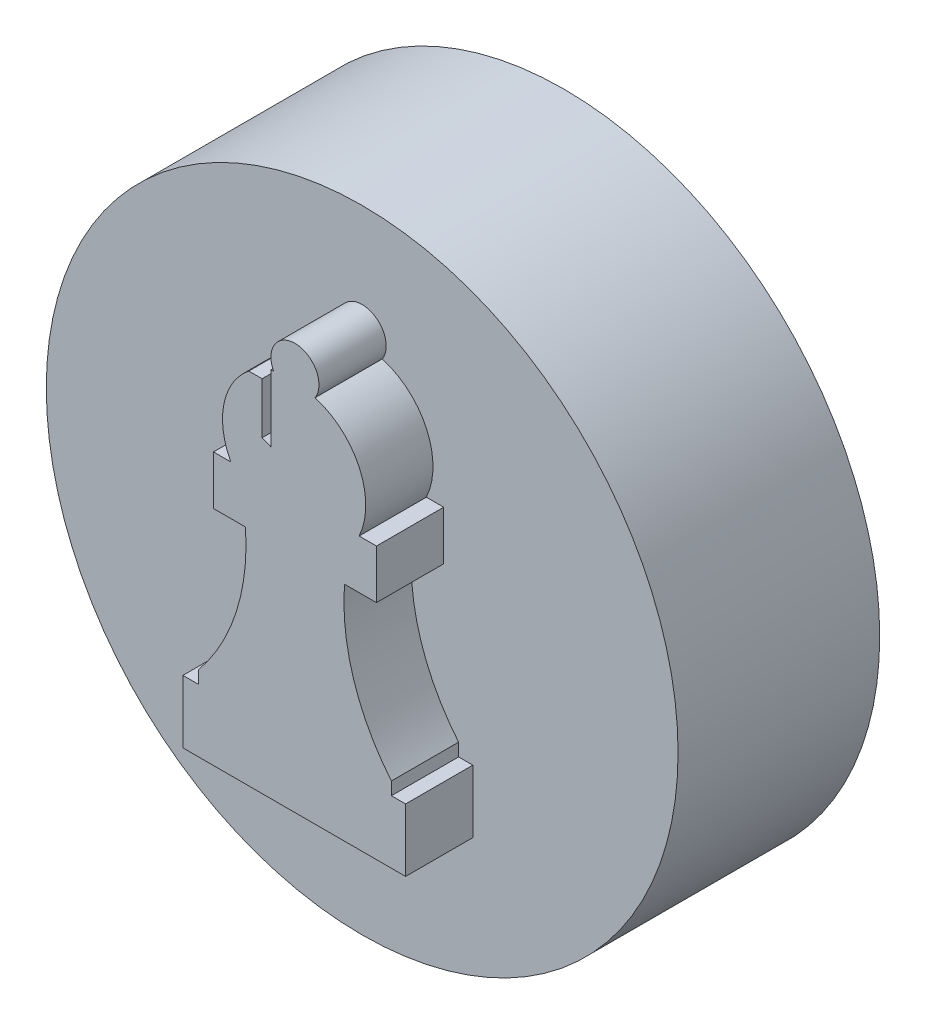
SolidWorks part; units mm, degrees
ref_plane "Front Plane" through (0, 0, 0) normal (0, 0, 1) x (1, 0, 0)
ref_plane "Top Plane" through (0, 0, 0) normal (0, 1, 0) x (1, 0, 0)
ref_plane "Right Plane" through (0, 0, 0) normal (1, 0, 0) x (0, 0, -1)
sketch "Sketch1" plane through (0, 0, 0) normal (0, 0, 1) x (1, 0, 0)
  circle A0 centre (0, 0) radius 8.763
  circle A1 centre (0, 0) radius 11.938
  dimension "D1" = 17.526
  dimension "D2" = 23.876
extrude "Boss-Extrude1" add sketch "Sketch1" along normal blind 5.08
sketch "Sketch2" plane through (0, 0, 5.08) normal (0, 0, 1) x (1, 0, 0)
  circle A0 centre (0, 0) radius 11.938
extrude "Boss-Extrude2" add sketch "Sketch2" along normal blind 2.54
sketch "Sketch3" plane through (0, 0, 7.62) normal (0, 0, 1) x (1, 0, 0)
  line L0 (76.4074, 247.7537) -> (417.7408, 247.7537) construction
  line L1 (0, 0) -> (0, 10.7108) construction
  line L30 (33.3333, 100.0554) -> (166.6667, 100.0554) construction
  line L31 (76.5513, 248.4132) -> (417.8847, 248.4132) construction
  line L32 (-3.6439, -4.2887) -> (-3.6439, -3.8053)
  line L33 (4.1807, -4.2887) -> (3.6439, -4.2887)
  line L34 (4.1807, -4.2887) -> (4.1807, -6.6617)
  line L35 (4.1807, -6.6617) -> (-4.2351, -6.6617)
  line L36 (-4.2351, -4.2887) -> (-4.2351, -6.6617)
  line L37 (-2.4252, 3.6017) -> (-3.0796, 3.6017)
  line L38 (-3.0796, 3.6017) -> (-3.0796, 1.7491)
  line L39 (-3.0796, 1.7491) -> (-1.8714, 1.7491)
  line L40 (-1.7443, 6.9155) -> (-1.2422, 6.9155)
  line L41 (-1.2422, 6.9155) -> (-1.2422, 4.9858)
  line L42 (-1.2422, 4.9858) -> (-0.9067, 4.8495)
  line L43 (-0.9067, 4.8495) -> (-0.9067, 7.3726)
  line L44 (-0.9067, 7.3726) -> (-0.8056, 7.3726)
  line L45 (2.4252, 3.6017) -> (3.0796, 3.6017)
  line L46 (3.0796, 3.6017) -> (3.0796, 1.7491)
  line L47 (3.0796, 1.7491) -> (1.8714, 1.7491)
  line L48 (3.6439, -4.2887) -> (3.6439, -3.8053)
  line L49 (-3.6439, -4.2887) -> (-4.2351, -4.2887)
  arc A10 (-3.6439, -3.8053) -> (-1.8714, 1.7491) centre (-9.6302, 1.165) ccw
  arc A11 (-1.7443, 6.9155) -> (-2.4252, 3.6017) centre (-0.0936, 4.8495) ccw
  arc A12 (0.7602, 7.2946) -> (2.4252, 3.6017) centre (0.0011, 4.7306) cw
  arc A13 (0.7602, 7.2946) -> (-0.8056, 7.3726) centre (0, 7.7888) ccw
  arc A14 (3.6439, -3.8053) -> (1.8714, 1.7491) centre (9.6302, 1.165) cw
  point P39 (2.4252, 3.6034)
extrude "Boss-Extrude4" add sketch "Sketch3" along normal blind 2.54 contours L40 L41 L42 L43 L44 A13 A12 L45 L46 L47 A14 L48 L33 L34 L35 L36 L49 L32 A10 L39 L38 L37 A11
